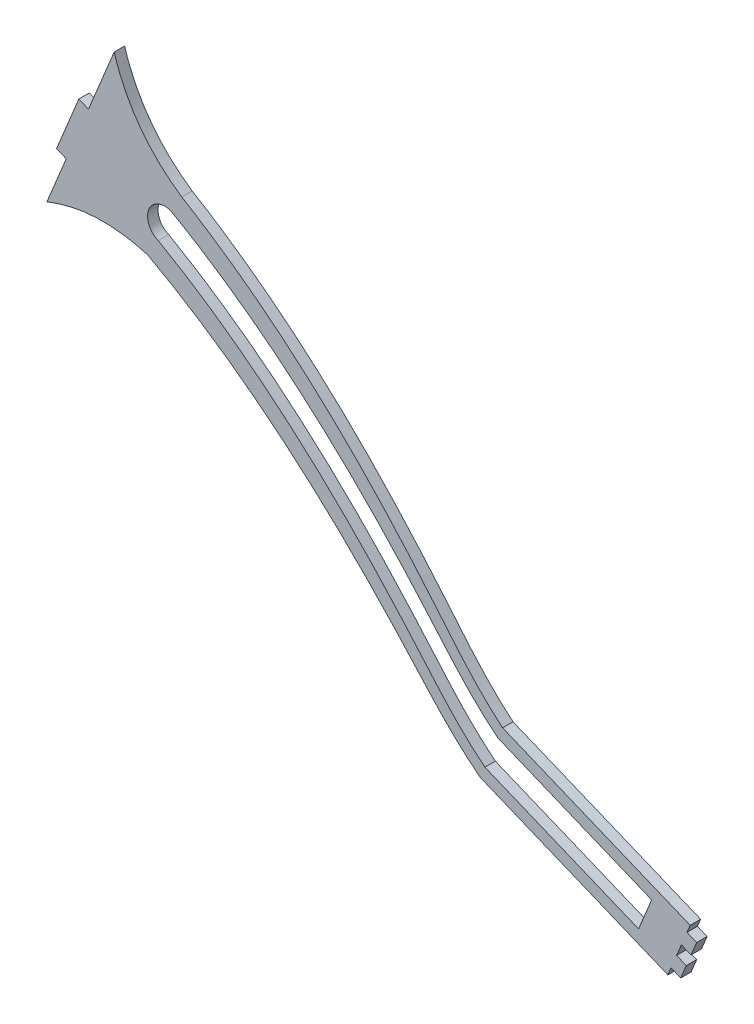
SolidWorks part; units mm, degrees
ref_plane "Front Plane" through (0, 0, 0) normal (0, 0, 1) x (1, 0, 0)
ref_plane "Top Plane" through (0, 0, 0) normal (0, 1, 0) x (1, 0, 0)
ref_plane "Right Plane" through (0, 0, 0) normal (1, 0, 0) x (0, 0, -1)
sketch "Sketch2" plane through (0, 0, 324.6091) normal (0, 0, 1) x (1, 0, 0)
  line L0 (-16.9001, -8.1832) -> (72.8165, -45.1124)
  line L1 (72.8165, -45.1124) -> (74.339, -41.4135)
  line L2 (83.4743, -19.2201) -> (-6.2423, 17.7091)
  line L3 (1.577, -0.6491) -> (-11.5712, 4.763) construction
  line L4 (-31.9742, 22.0287) -> (-36.491, 11.0554) construction
  line L5 (375.3074, 944.6533) -> (-8.45, 12.3457) construction
  line L6 (65.0498, -17.9083) -> (-8.45, 12.3457)
  line L7 (-11.5712, 4.763) -> (78.2012, -32.1893) construction
  line L8 (-14.6924, -2.8198) -> (58.8073, -33.0738)
  line L9 (58.8073, -33.0738) -> (65.0498, -17.9083)
  line L10 (-14.6924, -2.8198) -> (-393.3529, -922.7448) construction
  line L11 (-31.5661, 12.9932) -> (-986.2799, 405.9735) construction
  line L12 (-224.1829, 126.5929) -> (-214.9454, 149.0346)
  line L13 (74.339, -41.4135) -> (78.9627, -43.3167)
  line L14 (78.9627, -43.3167) -> (81.6271, -36.8436)
  line L15 (-208.9112, 176.8301) -> (-204.2876, 174.9269)
  line L16 (-219.569, 150.9378) -> (-214.9454, 149.0346)
  line L17 (-219.569, 150.9378) -> (-208.9112, 176.8301)
  line L18 (-204.2876, 174.9269) -> (-192.0222, 204.7247)
  line L19 (81.6271, -36.8436) -> (77.0035, -34.9405)
  line L20 (79.2873, -29.3921) -> (83.9109, -31.2953)
  line L21 (83.9109, -31.2953) -> (86.5754, -24.8222)
  line L22 (86.5754, -24.8222) -> (81.9518, -22.919)
  line L23 (81.9518, -22.919) -> (83.4743, -19.2201)
  line L24 (77.0035, -34.9405) -> (79.2873, -29.3921)
  arc A0 (-159.6673, 160.8235) -> (-175.9119, 128.6971) centre (-167.8281, 144.7798) ccw construction
  arc A1 (-164.7069, 152.3625) -> (-170.9494, 137.197) centre (-167.8281, 144.7798) ccw
  spline S0 degree 3 poles (-14.6924, -2.8198) (-27.809, 7.6384) (-72.367, 61.955) (-124.0787, 110.4292) (-170.9494, 137.197) knots 0 0 0 0 0.237148 1 1 1 1
  spline S1 degree 3 poles (-11.5712, 4.763) (-24.6878, 15.2212) (-69.2458, 69.5377) (-120.9575, 118.0119) (-167.8281, 144.7798) knots 0 0 0 0 0.237148 1 1 1 1 construction
  spline S2 degree 3 poles (-8.45, 12.3457) (-21.5666, 22.8039) (-66.1246, 77.1205) (-117.8363, 125.5947) (-164.7069, 152.3625) knots 0 0 0 0 0.237148 1 1 1 1
  spline S3 degree 3 poles (-6.2423, 17.7091) (-19.1471, 28.4276) (-62.6097, 83.6245) (-113.3415, 133.1235) (-159.6673, 160.8235) knots 0 0 0 0 0.237148 1 1 1 1
  spline S4 degree 3 poles (-16.9001, -8.1832) (-30.2222, 2.012) (-75.852, 55.4313) (-128.518, 102.8671) (-175.9119, 128.6971) knots 0 0 0 0 0.237148 1 1 1 1
  spline S5 degree 2 poles (-175.9119, 128.6971) (-200.798, 136.066) (-224.1829, 126.5929) knots 0 0 0 1 1 1
  spline S6 degree 2 poles (-192.0222, 204.7247) (-183.5257, 177.0768) (-159.6673, 160.8235) knots 0 0 0 1 1 1
  dimension "D1" = 14
  dimension "D9" = 18
  dimension "D8" = 8.2
  dimension "D2" = 14
  dimension "D3" = 8.2
  dimension "D4" = 7
  dimension "D5" = 8.2
  dimension "D6" = 97.0198
  dimension "D7" = 79.4828
  dimension "D10" = 4
  dimension "D11" = 5
  dimension "D12" = 5
  dimension "D13" = 7
  dimension "D14" = 5
  dimension "D15" = 4
extrude "Boss-Extrude1" add sketch "Sketch2" against normal blind 5
ref_plane "Plane1" through (0, 0, 322.1091) normal (0, 0, 1) x (1, 0, 0)
sketch "Sketch3" plane through (0, 0, 322.1091) normal (0, 0, 1) x (1, 0, 0)
  line L0 (184946.5517, -76127.887) -> (-11.5712, 4.763) construction
  line L1 (78.2012, -32.1893) -> (-10.2271, 4.2097)
  arc A0 (-10.2271, 4.2097) -> (-12.7508, 5.7155) centre (-6.4207, 13.4569) cw
  spline S0 degree 3 poles (1657.7295, 1090.3652) (103.7075, -181.553) (-104.9422, 227.4638) (-605.4971, 398.0877) (-1764.9346, -986.6174) knots -1.662687 -1.662687 -1.662687 -1.662687 0.237148 4.725156 4.725156 4.725156 4.725156 only from (-11.5712, 4.763) to (-167.8281, 144.7798) construction
  spline S1 degree 3 poles (-12.7508, 5.7155) (-25.3254, 15.9976) (-69.6156, 69.8843) (-120.9575, 118.0119) (-167.8281, 144.7798) knots 0.007151 0.007151 0.007151 0.007151 0.237148 1 1 1 1
  dimension "D1" = 10
